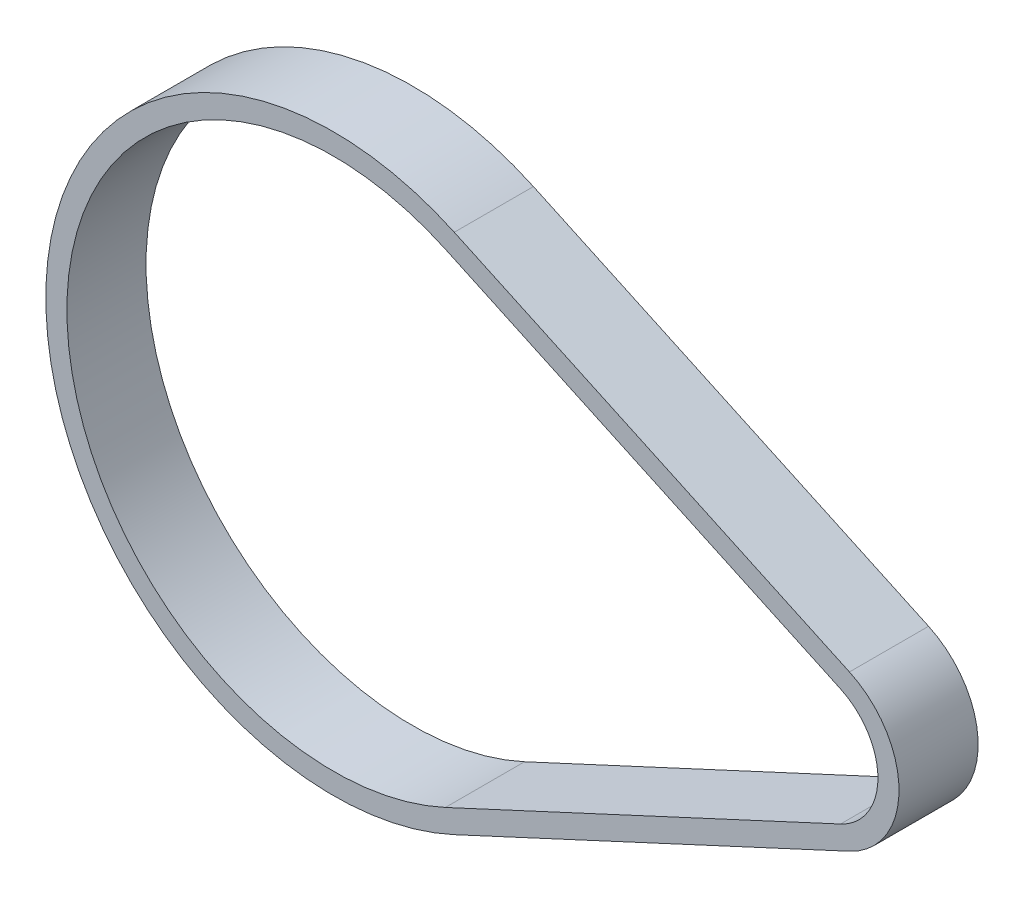
SolidWorks part; units mm, degrees
ref_plane "Front Plane" through (0, 0, 0) normal (0, 0, 1) x (1, 0, 0)
ref_plane "Top Plane" through (0, 0, 0) normal (0, 1, 0) x (1, 0, 0)
ref_plane "Right Plane" through (0, 0, 0) normal (1, 0, 0) x (0, 0, -1)
sketch "Sketch1" plane through (0, 0, 0) normal (0, 0, 1) x (1, 0, 0)
  line L0 (-22.75, 0) -> (22.75, 0) construction
  line L1 (-11.287, 24.7217) -> (26.1615, 7.3575)
  line L2 (-12.1284, 22.9073) -> (25.3202, 5.5431)
  line L3 (25.3202, -5.5431) -> (-12.1284, -22.9073)
  line L4 (26.1615, -7.3575) -> (-11.287, -24.7217)
  circle A0 centre (22.75, 0) radius 6.11 construction
  circle A1 centre (-22.75, 0) radius 25.25 construction
  circle A2 centre (-22.75, 0) radius 27.25 construction
  circle A3 centre (22.75, 0) radius 8.11 construction
  arc A4 (-11.287, 24.7217) -> (-11.287, -24.7217) centre (-22.75, 0) ccw
  arc A5 (26.1615, 7.3575) -> (26.1615, -7.3575) centre (22.75, 0) cw
  arc A6 (25.3202, 5.5431) -> (25.3202, -5.5431) centre (22.75, 0) cw
  arc A7 (-12.1284, 22.9073) -> (-12.1284, -22.9073) centre (-22.75, 0) ccw
  point P4 (0, 0)
extrude "Boss-Extrude1" add sketch "Sketch1" along normal blind 7.5
